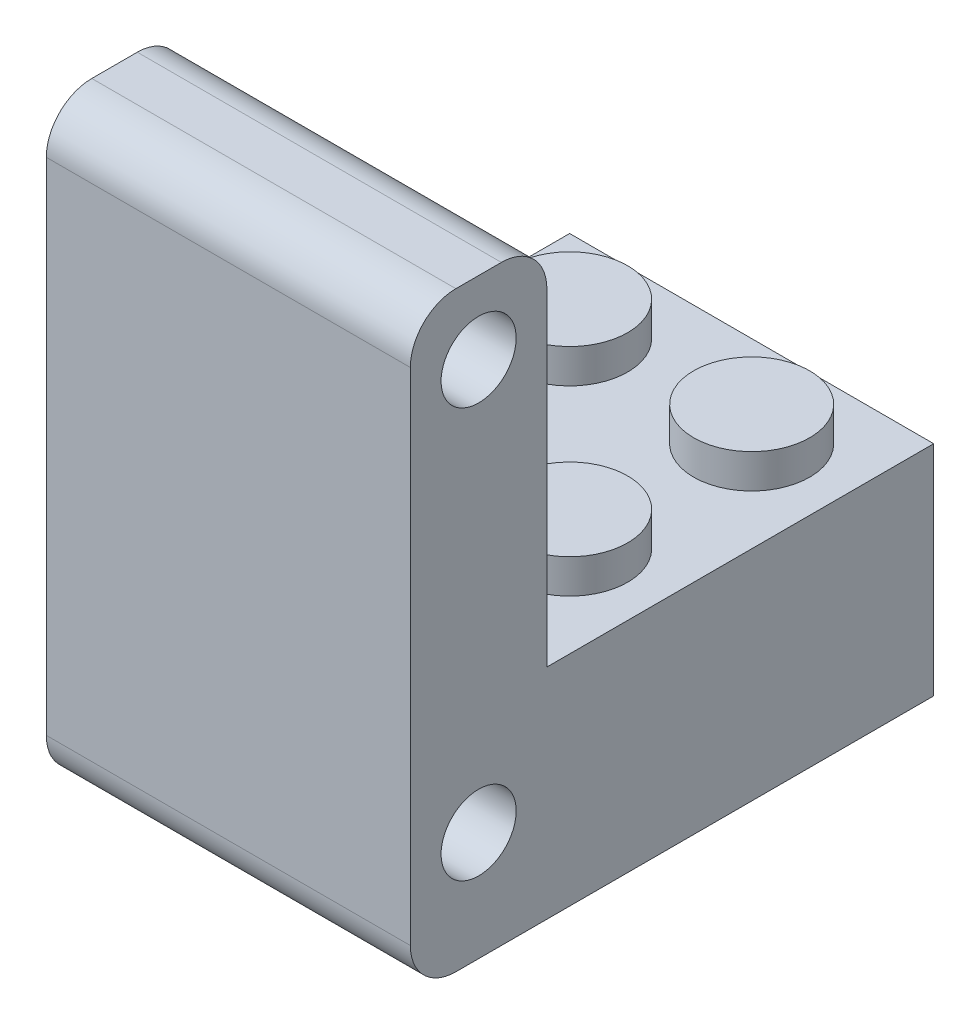
SolidWorks part; units mm, degrees
material "ABS"
ref_plane "Front Plane" through (0, 0, 0) normal (0, 0, 1) x (1, 0, 0)
ref_plane "Top Plane" through (0, 0, 0) normal (0, 1, 0) x (1, 0, 0)
ref_plane "Right Plane" through (0, 0, 0) normal (1, 0, 0) x (0, 0, -1)
sketch "Sketch1" plane through (76, 0, 0) normal (1, 0, 0) x (0, 0, -1)
  line L0 (-39.3671, -19.7967) -> (-39.3671, -29.3967) construction
  line L1 (-39.3671, -19.7967) -> (-39.3671, -29.3967) construction
  line L2 (-39.3671, -29.3967) -> (-62.3671, -29.3967)
  line L3 (-62.3671, -29.3967) -> (-62.3671, -3.3967)
  line L4 (-62.3671, -3.3967) -> (-56.3671, -3.3967)
  line L5 (-56.3671, -3.3967) -> (-56.3671, -19.7967)
  line L6 (-56.3671, -19.7967) -> (-39.3671, -19.7967)
  line L7 (-39.3671, -19.7967) -> (-39.3671, -29.3967)
  arc A0 (-59.3671, -25.9217) -> (-59.3671, -23.2717) centre (-59.3671, -24.5967) ccw construction
  arc A1 (-59.3671, -7.9217) -> (-59.3671, -5.2717) centre (-59.3671, -6.5967) ccw construction
  arc A2 (-59.3671, -25.9217) -> (-59.3671, -23.2717) centre (-59.3671, -24.5967) ccw construction
  arc A3 (-59.3671, -7.9217) -> (-59.3671, -5.2717) centre (-59.3671, -6.5967) ccw construction
  circle A4 centre (-59.3671, -24.5967) radius 1.65
  circle A5 centre (-59.3671, -6.5967) radius 1.65
  dimension "D4" = 3.3
  dimension "D1" = 6
  dimension "D2" = 17
  dimension "D3" = 26
extrude "Boss-Extrude1" add sketch "Sketch1" against normal blind 16
sketch "Sketch2" plane through (0, -19.7967, 0) normal (0, 1, 0) x (1, 0, 0)
  line L4 (76, -56.3671) -> (76, -39.3671)
  line L5 (76, -39.3671) -> (60, -39.3671)
  line L6 (60, -39.3671) -> (60, -56.3671)
  line L7 (60, -56.3671) -> (76, -56.3671)
  line L8 (76, -56.3671) -> (76, -39.3671)
  line L9 (76, -39.3671) -> (60, -39.3671)
  line L10 (60, -39.3671) -> (60, -56.3671)
  line L11 (60, -56.3671) -> (76, -56.3671)
  circle A0 centre (64, -43.3671) radius 2.55
  circle A1 centre (72, -43.3671) radius 2.55
  circle A2 centre (72, -51.3671) radius 2.55
  circle A3 centre (64, -51.3671) radius 2.55
  circle A4 centre (64, -35.3671) radius 2.4 construction
  circle A5 centre (72, -35.3671) radius 2.4 construction
  circle A6 centre (64, -35.3671) radius 2.4
  circle A7 centre (72, -35.3671) radius 2.4
  dimension "D4" = 5.1
  dimension "D2" = 8
  dimension "D3" = 8
  dimension "D1" = 0
extrude "Boss-Extrude2" add sketch "Sketch2" along normal blind 1.5 contours A3 | A0 | A1 | A2
fillet "Fillet1" radius 2 3 edges at (68, -29.3967, 62.3671) (68, -3.3967, 62.3671) (68, -3.3967, 56.3671)
sketch "Sketch3" plane through (0, -19.7967, 0) normal (0, 1, 0) x (1, 0, 0)
  line L0 (60, -39.3671) -> (76, -56.3671) construction
  line L1 (76, -39.3671) -> (60, -56.3671) construction
  line L2 (66.8588, -49.0671) -> (69.1412, -49.0671)
  line L3 (67.0588, -48.8671) -> (68.9412, -48.8671)
  line L4 (76, -56.3671) -> (76, -39.3671)
  line L5 (76, -39.3671) -> (60, -39.3671)
  line L6 (60, -39.3671) -> (60, -56.3671)
  line L7 (60, -56.3671) -> (76, -56.3671)
  line L8 (76, -56.3671) -> (76, -39.3671) construction
  line L9 (76, -39.3671) -> (60, -39.3671) construction
  line L10 (60, -39.3671) -> (60, -56.3671) construction
  line L12 (67.0588, -48.8671) -> (67.0588, -46.8671)
  line L13 (67.0588, -46.8671) -> (68.9412, -46.8671)
  line L14 (68.9412, -48.8671) -> (68.9412, -46.8671)
  line L15 (67.0588, -48.8671) -> (68.9412, -46.8671) construction
  line L16 (67.0588, -46.8671) -> (68.9412, -48.8671) construction
  line L17 (69.1412, -49.0671) -> (69.1412, -46.6671)
  line L18 (66.8588, -46.6671) -> (69.1412, -46.6671)
  line L19 (66.8588, -49.0671) -> (66.8588, -46.6671)
  line L24 (60, -56.3671) -> (76, -56.3671)
  point P2 (68, -47.8671)
  dimension "D2" = 2
  dimension "D1" = 0
  dimension "D3" = 0.2
